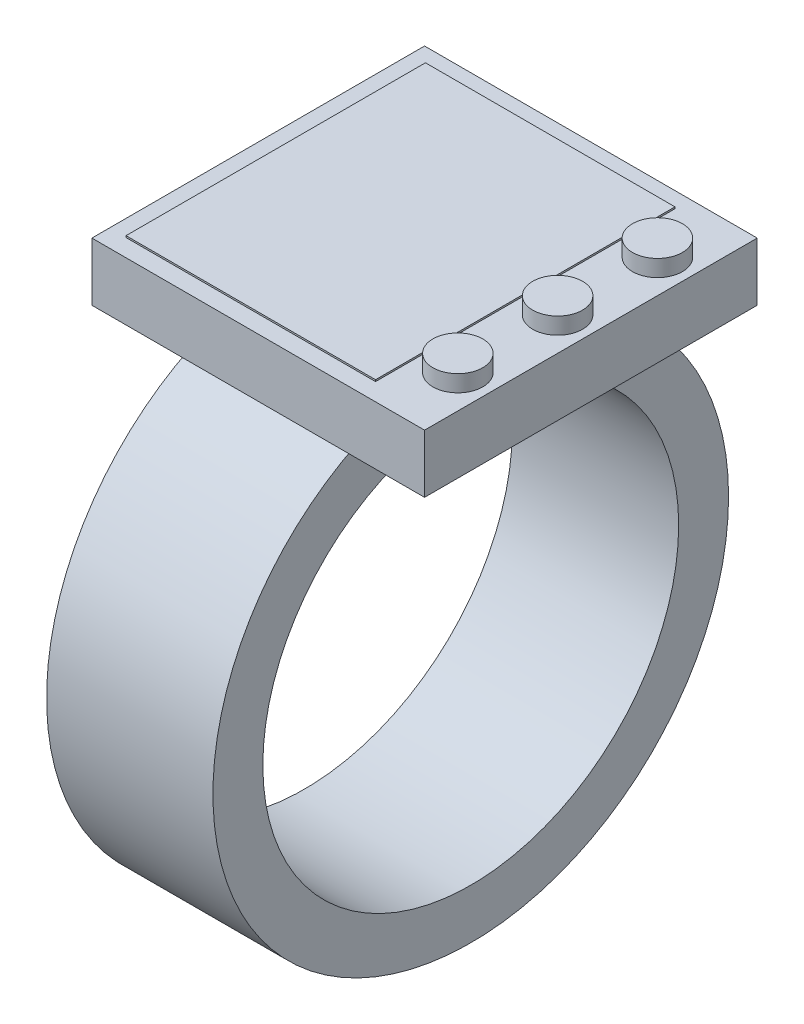
SolidWorks part; units mm, degrees
ref_plane "Front Plane" through (0, 0, 0) normal (0, 0, 1) x (1, 0, 0)
ref_plane "Top Plane" through (0, 0, 0) normal (0, 1, 0) x (1, 0, 0)
ref_plane "Right Plane" through (0, 0, 0) normal (1, 0, 0) x (0, 0, -1)
sketch "Sketch1" plane through (0, 0, 0) normal (1, 0, 0) x (0, 0, -1)
  circle A0 centre (0, 0) radius 31.75
  circle A1 centre (0, 0) radius 39.37
  dimension "D1" = 78.74
  dimension "D2" = 63.5
extrude "Boss-Extrude1" add sketch "Sketch1" along normal blind 25.4
ref_plane "Plane1" through (0, 39.37, 0) normal (0, 1, 0) x (1, 0, 0)
sketch "Sketch4" plane through (0, 39.37, 0) normal (0, 1, 0) x (1, 0, 0)
  line L1 (-9.1046, 27.4502) -> (41.6954, 27.4502)
  line L2 (-9.1046, 27.4502) -> (-9.1046, -23.3498)
  line L3 (-9.1046, -23.3498) -> (41.6954, -23.3498)
  line L4 (41.6954, 27.4502) -> (41.6954, -23.3498)
  dimension "D1" = 50.8
  dimension "D2" = 50.8
extrude "Boss-Extrude3" add sketch "Sketch4" along normal blind 8.89 separate body
sketch "Sketch5" plane through (0, 48.26, 0) normal (0, 1, 0) x (1, 0, 0)
  line L0 (-9.1046, 27.4502) -> (-6.5646, 27.4502)
  line L1 (41.6954, 27.4502) -> (-9.1046, 27.4502) construction
  line L2 (-6.5646, 27.4502) -> (-6.5646, 25.0445)
  line L3 (41.6954, -23.3498) -> (41.6954, -16.9619)
  line L4 (-6.5646, 25.0445) -> (31.5354, 25.0445)
  line L5 (-6.5646, 25.0445) -> (-6.5646, -20.6755)
  line L6 (-6.5646, -20.6755) -> (31.5354, -20.6755)
  line L7 (31.5354, 25.0445) -> (31.5354, -20.6755)
  line L8 (41.6954, -23.3498) -> (41.6954, 27.4502) construction
  line L9 (41.6954, -16.9619) -> (36.6154, -16.9619)
  line L10 (41.6954, 27.4502) -> (41.6954, 21.1002)
  line L11 (41.6954, 21.1002) -> (36.6154, 21.1002)
  line L12 (36.6154, 2.0881) -> (41.6954, 2.0881)
  line L13 (36.6154, 2.0881) -> (36.6154, -16.9619)
  circle A0 centre (36.6154, 21.1002) radius 3.81
  circle A1 centre (36.6154, 2.0881) radius 3.81
  circle A2 centre (36.6154, -16.9619) radius 3.81
  dimension "D1" = 45.72
  dimension "D2" = 38.1
extrude "Boss-Extrude4" add sketch "Sketch5" along normal blind 0.254 contours L5 L4 L7 L6
sketch "Sketch7" plane through (0, 48.26, 0) normal (0, 1, 0) x (1, 0, 0)
  line L0 (41.6954, 27.4502) -> (36.6154, 27.4502)
  line L1 (41.6954, 27.4502) -> (-9.1046, 27.4502) construction
  line L2 (36.6154, 27.4502) -> (36.6154, 17.2902)
  line L3 (41.6954, -23.3498) -> (36.6154, -23.3498)
  line L4 (-9.1046, -23.3498) -> (41.6954, -23.3498) construction
  line L5 (36.6154, -23.3498) -> (36.6154, -13.1898)
  line L6 (41.6954, 2.0502) -> (36.6154, 2.0502)
  line L7 (41.6954, -23.3498) -> (41.6954, 27.4502) construction
  circle A0 centre (36.6154, 17.2902) radius 3.81
  circle A1 centre (36.6154, -13.1898) radius 3.81
  circle A2 centre (36.6154, 2.0502) radius 3.81
extrude "Boss-Extrude5" add sketch "Sketch7" along normal blind 2.54 contours A0 | A1 | A2
